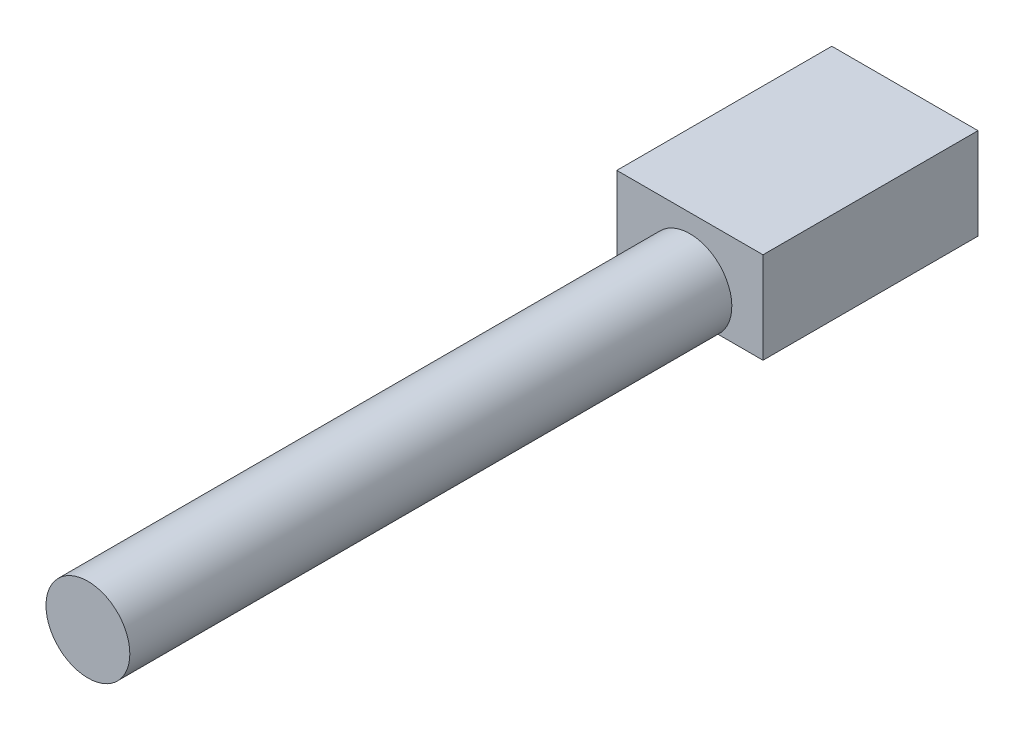
SolidWorks part; units mm, degrees
ref_plane "정면" through (0, 0, 0) normal (0, 0, 1) x (1, 0, 0)
ref_plane "윗면" through (0, 0, 0) normal (0, 1, 0) x (1, 0, 0)
ref_plane "우측면" through (0, 0, 0) normal (1, 0, 0) x (0, 0, -1)
sketch "스케치1" plane through (0, 0, 0) normal (0, 0, 1) x (1, 0, 0)
  circle A0 centre (0, 0) radius 9.75
  dimension "D1" = 19.5
extrude "보스-돌출1" add sketch "스케치1" along normal blind 140
sketch "스케치2" plane through (0, 0, 0) normal (0, 0, 1) x (1, 0, 0)
  line L1 (17, 14) -> (-17, 14)
  line L2 (17, 14) -> (17, -10)
  line L3 (17, -10) -> (-17, -10)
  line L4 (-17, 14) -> (-17, -10)
  point P0 (0, 0)
  dimension "D1" = 34
  dimension "D2" = 24
  dimension "D3" = 10
extrude "보스-돌출2" add sketch "스케치2" against normal blind 50
sketch "스케치3" plane through (0, 0, 0) normal (0, 0, 1) x (1, 0, 0)
  line L1 (-17, -7.25) -> (-6.5192, -7.25)
  line L2 (-17, 14) -> (-17, -10) construction
  line L3 (17, -10) -> (17, 14) construction
  line L4 (17, -7.25) -> (17, -10)
  line L5 (17, -10) -> (-17, -10)
  line L6 (-17, -10) -> (-17, -7.25)
  line L7 (6.5192, -7.25) -> (17, -7.25)
  circle A1 centre (0, 0) radius 9.75
  point P1 (0, -9.75)
  circle M5 centre (0, 0) radius 9.75
  line M6 (-17, 14) -> (-17, -10)
  line M7 (-17, -10) -> (17, -10)
  line M8 (17, -10) -> (17, 14)
  dimension "D2" = 9.75
extrude "컷-돌출1" cut sketch "스케치3" against normal up to next contours L7 L1 M5 M6 M7 M8
